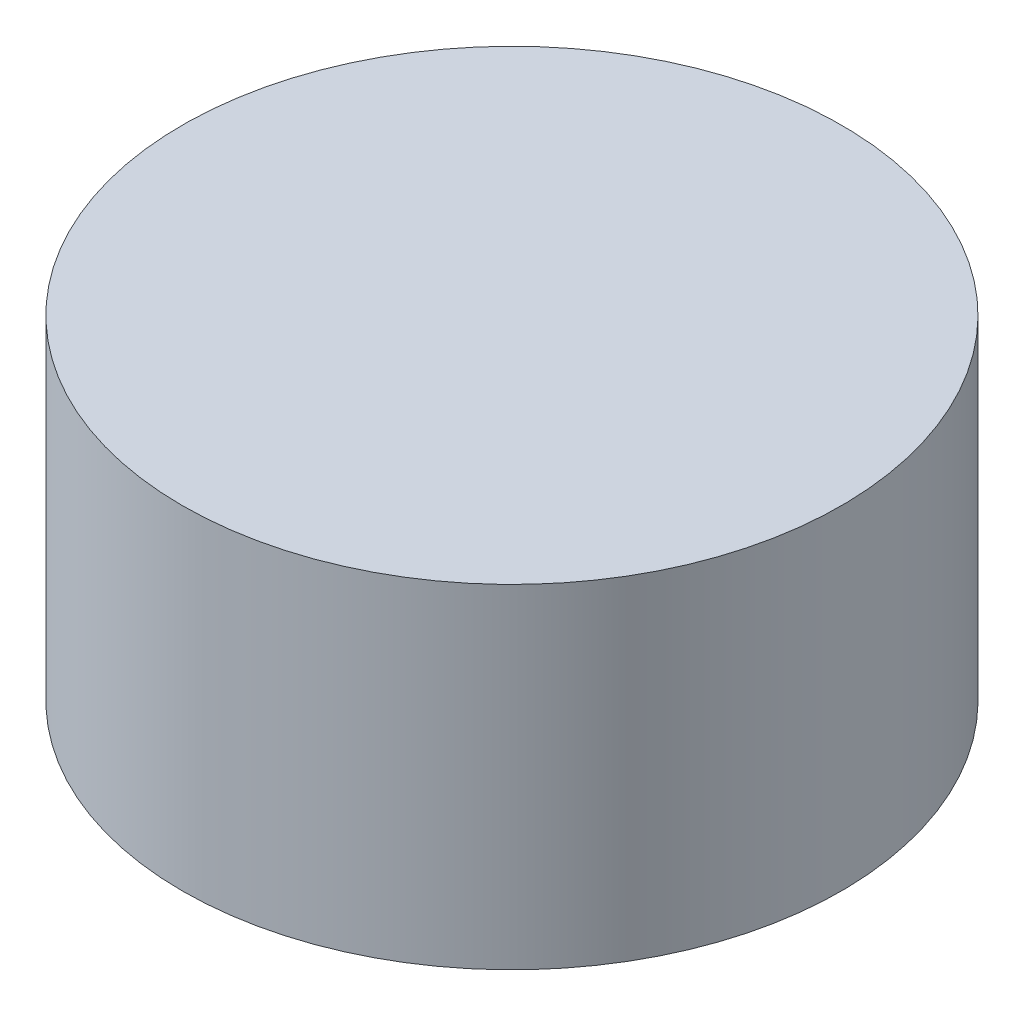
SolidWorks part; units mm, degrees
ref_plane "Front Plane" through (0, 0, 0) normal (0, 0, 1) x (1, 0, 0)
ref_plane "Top Plane" through (0, 0, 0) normal (0, 1, 0) x (1, 0, 0)
ref_plane "Right Plane" through (0, 0, 0) normal (1, 0, 0) x (0, 0, -1)
sketch "Sketch1" plane through (0, 0, 0) normal (0, 1, 0) x (1, 0, 0)
  circle A0 centre (0, 0) radius 3.95
  dimension "D1" = 7.9
extrude "Boss-Extrude1" add sketch "Sketch1" along normal blind 4
